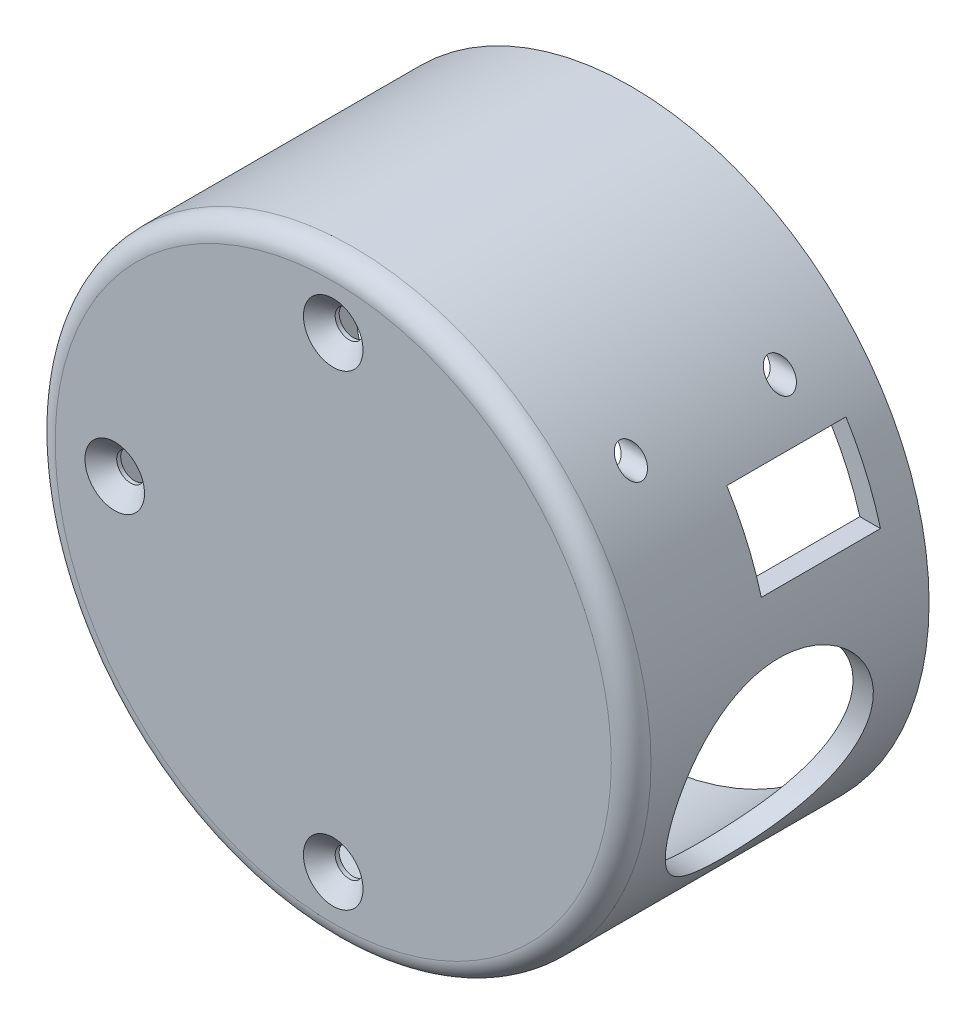
SolidWorks part; units mm, degrees
ref_plane "Alzado" through (0, 0, 0) normal (0, 0, 1) x (1, 0, 0)
ref_plane "Planta" through (0, 0, 0) normal (0, 1, 0) x (1, 0, 0)
ref_plane "Vista lateral" through (0, 0, 0) normal (1, 0, 0) x (0, 0, -1)
sketch "Croquis1" plane through (0, 0, 0) normal (0, 0, 1) x (1, 0, 0)
  circle A0 centre (0, 0) radius 30
  dimension "D1" = 60
extrude "Saliente-Extruir1" add sketch "Croquis1" along normal blind 30
shell "Vaciado1" thickness 2
fillet "Redondeo1" radius 2 2 edges at (30, 0, 30) (28, 0, 28)
sketch "Croquis2" plane through (0, 0, 30) normal (0, 0, 1) x (1, 0, 0)
  line L0 (-30, 0) -> (30, 0) construction
  circle A0 centre (0, 0) radius 30 construction
ref_plane "Plano1" through (30, 0, 30) normal (1, 0, 0) x (0, 0, -1)
sketch "Croquis3" plane through (30, 0, 30) normal (1, 0, 0) x (0, 0, -1)
  line L0 (0, 0) -> (30, 0) construction
  line L1 (0, 28) -> (0, -28) construction
  line L2 (30, -30) -> (30, 30) construction
  circle A0 centre (15, -7.5) radius 10.1
  dimension "D2" = 20.2
  dimension "D1" = 7.5
  dimension "D3" = 15
extrude "Cortar-Extruir1" cut sketch "Croquis3" against normal up to next
sketch "Croquis5" plane through (0, 0, 30) normal (0, 0, 1) x (1, 0, 0)
  circle A0 centre (-22, 0) radius 1.25 construction
  circle A1 centre (0, -23.5) radius 1.25 construction
  circle A2 centre (0, 23.5) radius 1.25 construction
  circle A3 centre (-22, 0) radius 1.25 construction
  circle A4 centre (0, -23.5) radius 1.25 construction
  circle A5 centre (0, 23.5) radius 1.25 construction
  circle A6 centre (0, 23.5) radius 1.4
  circle A7 centre (-22, 0) radius 1.4
  circle A8 centre (0, -23.5) radius 1.4
  dimension "D1" = 0.15
extrude "Cortar-Extruir2" cut sketch "Croquis5" against normal up to next
chamfer "Chaflán1" distance 1.6 angle 45 3 edges at (1.4, -23.5, 30) (-20.6, 0, 30) (1.4, 23.5, 30)
sketch "Croquis7" plane through (0, 0, 0) normal (0, 0, 1) x (1, 0, 0)
  line L0 (0, 0) -> (30, 0) construction
  line L1 (0, 0) -> (28.9778, 7.7646) construction
  line L2 (0, 0) -> (15, 25.9808) construction
  circle A0 centre (0, 0) radius 30 construction
  dimension "D1" = 45
  dimension "D2" = 15
ref_plane "Plano2" through (30, 0, 0) normal (1, 0, 0) x (0, 0, -1)
sketch "Croquis11" plane through (0, 0, 0) normal (1, 0, 0) x (0, 0, -1)
  line L3 (-3.85, 7.8422) -> (-3.85, 15.8422)
  line L4 (-3.85, 15.8422) -> (-15.85, 15.8422)
  line L5 (-15.85, 15.8422) -> (-15.85, 7.8422)
  line L6 (-3.85, 7.8422) -> (-15.85, 7.8422)
  circle A2 centre (-22.5, 19.8422) radius 1.25
  circle A3 centre (-7.5, 19.8422) radius 1.25
extrude "Cortar-Extruir3" cut sketch "Croquis11" along normal through all
